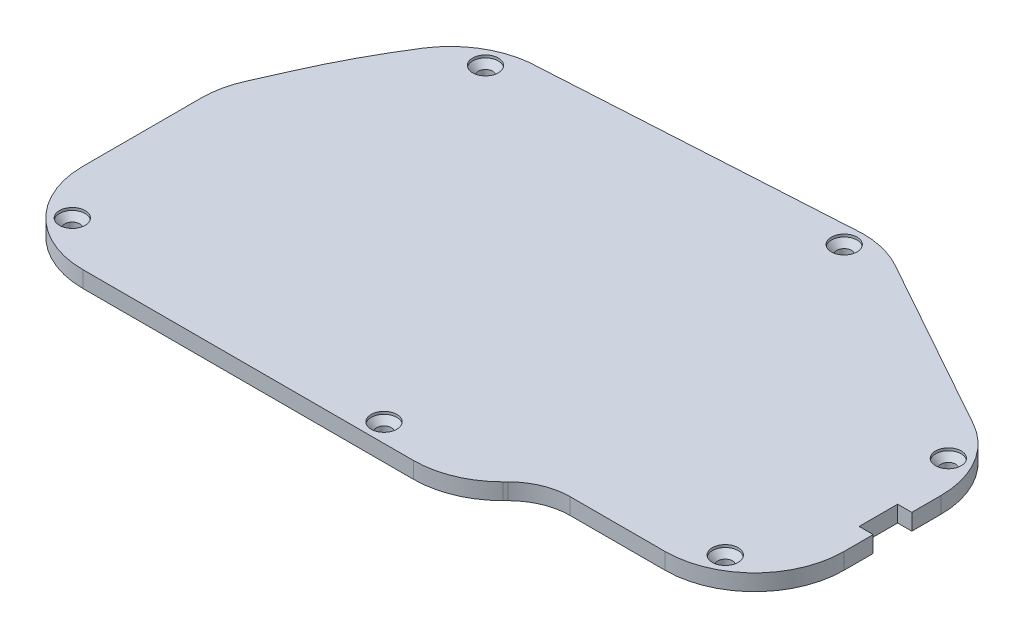
SolidWorks part; units mm, degrees
ref_plane "Front Plane" through (0, 0, 0) normal (0, 0, 1) x (1, 0, 0)
ref_plane "Top Plane" through (0, 0, 0) normal (0, 1, 0) x (1, 0, 0)
ref_plane "Right Plane" through (0, 0, 0) normal (1, 0, 0) x (0, 0, -1)
sketch "Sketch2" plane through (0, 0, 0) normal (0, 1, 0) x (1, 0, 0)
  line L7 (-257.8256, -105.63) -> (-193.4944, -105.63) construction
  line L8 (-181.1201, -100.5044) -> (-180.6101, -99.9944) construction
  line L9 (-172.1248, -96.4797) -> (-153.6496, -96.4797) construction
  line L10 (-136.1496, -78.9797) -> (-136.1496, -60.0821) construction
  line L11 (-145.1341, -44.7936) -> (-179.4485, -25.681) construction
  line L12 (-187.9639, -23.4695) -> (-247.3805, -26.968) construction
  line L13 (-271.0251, -51.648) -> (-273.8196, -57.9411) construction
  line L14 (-275.3256, -65.0434) -> (-275.3256, -88.13) construction
  line L15 (-145.1828, -44.881) -> (-179.4971, -25.7684)
  line L16 (-187.961, -23.5695) -> (-247.3776, -27.068)
  line L17 (-270.9337, -51.6886) -> (-273.7282, -57.9817)
  line L18 (-275.2256, -65.0434) -> (-275.2256, -88.13)
  line L19 (-257.8256, -105.53) -> (-193.4944, -105.53)
  line L20 (-181.1908, -100.4337) -> (-180.6808, -99.9237)
  line L21 (-172.1248, -96.3797) -> (-153.6496, -96.3797)
  line L22 (-136.2496, -78.9797) -> (-136.2496, -73.2809)
  line L23 (-136.2496, -69.5309) -> (-138.9996, -69.5309) construction
  line L24 (-138.9996, -65.7809) -> (-138.9996, -73.2809)
  line L25 (-138.9996, -65.7809) -> (-136.2496, -65.7809)
  line L26 (-138.9996, -73.2809) -> (-136.2496, -73.2809)
  line L27 (-136.2496, -78.9797) -> (-136.2496, -60.0821) construction
  line L28 (-136.2496, -65.7809) -> (-136.2496, -60.0821)
  line L29 (-136.2496, -65.7809) -> (-136.2496, -73.2809) construction
  circle A15 centre (-147.2076, -91.1273) radius 1.425
  circle A16 centre (-141.795, -53.1155) radius 1.425
  circle A17 centre (-187.9639, -27.2195) radius 1.425
  arc A18 (-275.3256, -88.13) -> (-257.8256, -105.63) centre (-257.8256, -88.13) ccw construction
  arc A19 (-193.4944, -105.63) -> (-181.1201, -100.5044) centre (-193.4944, -88.13) ccw construction
  arc A20 (-172.1248, -96.4797) -> (-180.6101, -99.9944) centre (-172.1248, -108.4797) ccw construction
  arc A21 (-153.6496, -96.4797) -> (-136.1496, -78.9797) centre (-153.6496, -78.9797) ccw construction
  arc A22 (-136.1496, -60.0821) -> (-145.1341, -44.7936) centre (-153.6496, -60.0821) ccw construction
  arc A23 (-179.4485, -25.681) -> (-187.9639, -23.4695) centre (-187.9639, -40.9695) ccw construction
  arc A24 (-247.3805, -26.968) -> (-262.1548, -35.0887) centre (-247.3805, -44.468) ccw construction
  arc A25 (-262.1548, -35.0887) -> (-271.0251, -51.648) centre (-154.7153, -103.2964) ccw construction
  arc A26 (-273.8196, -57.9411) -> (-275.3256, -65.0434) centre (-257.8256, -65.0434) ccw construction
  circle A27 centre (-253.0515, -31.942) radius 1.425
  circle A28 centre (-267.5484, -97.8527) radius 1.425
  circle A29 centre (-202.8547, -101.88) radius 1.425
  arc A30 (-179.4971, -25.7684) -> (-187.961, -23.5695) centre (-187.9639, -40.9695) ccw
  arc A31 (-247.3776, -27.068) -> (-262.0703, -35.1423) centre (-247.3805, -44.468) ccw
  arc A32 (-262.0703, -35.1423) -> (-270.9337, -51.6886) centre (-154.7153, -103.2964) ccw
  arc A33 (-273.7282, -57.9817) -> (-275.2256, -65.0434) centre (-257.8256, -65.0434) ccw
  arc A34 (-275.2256, -88.13) -> (-257.8256, -105.53) centre (-257.8256, -88.13) ccw
  arc A35 (-193.4944, -105.53) -> (-181.1908, -100.4337) centre (-193.4944, -88.13) ccw
  arc A36 (-172.1248, -96.3797) -> (-180.6808, -99.9237) centre (-172.1248, -108.4797) ccw
  arc A37 (-153.6496, -96.3797) -> (-136.2496, -78.9797) centre (-153.6496, -78.9797) ccw
  arc A38 (-136.2496, -60.0821) -> (-145.1828, -44.881) centre (-153.6496, -60.0821) ccw
  point P69 (-138.9996, -69.5309)
  dimension "D2" = 7.5
  dimension "D1" = 0.1
extrude "Boss-Extrude1" add sketch "Sketch2" along normal blind 3.175
sketch "Sketch3" plane through (0, 3.175, 0) normal (0, 1, 0) x (1, 0, 0)
  circle A0 centre (-253.0515, -31.942) radius 2.5
  circle A1 centre (-187.9639, -27.2195) radius 2.5
  circle A2 centre (-141.795, -53.1155) radius 2.5
  circle A3 centre (-147.2076, -91.1273) radius 2.5
  circle A4 centre (-202.8547, -101.88) radius 2.5
  circle A5 centre (-267.5484, -97.8527) radius 2.5
extrude "Cut-Extrude1" cut sketch "Sketch3" against normal blind 0.5
sketch "Sketch4" plane through (0, 2.675, 0) normal (0, 1, 0) x (1, 0, 0)
  circle A0 centre (-267.5484, -97.8527) radius 2.5 construction
  circle A1 centre (-202.8547, -101.88) radius 2.5 construction
  circle A2 centre (-147.2076, -91.1273) radius 2.5 construction
  circle A3 centre (-141.795, -53.1155) radius 2.5 construction
  circle A4 centre (-187.9639, -27.2195) radius 2.5 construction
  circle A5 centre (-253.0515, -31.942) radius 2.5 construction
  circle A6 centre (-267.5484, -97.8527) radius 2.5
  circle A7 centre (-202.8547, -101.88) radius 2.5
  circle A8 centre (-147.2076, -91.1273) radius 2.5
  circle A9 centre (-141.795, -53.1155) radius 2.5
  circle A10 centre (-187.9639, -27.2195) radius 2.5
  circle A11 centre (-253.0515, -31.942) radius 2.5
extrude "Cut-Extrude2" cut sketch "Sketch4" against normal blind 1.2 draft 42
